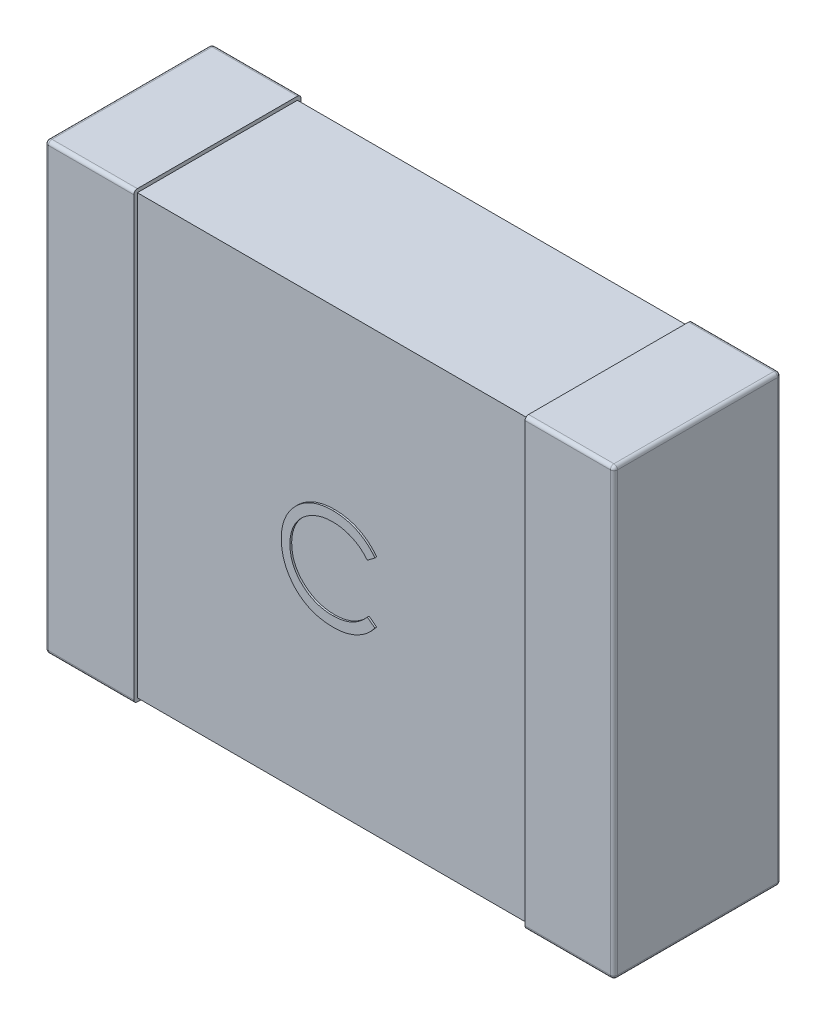
SolidWorks part; units mm, degrees
ref_plane "前视基准面" through (0, 0, 0) normal (0, 0, 1) x (1, 0, 0)
ref_plane "上视基准面" through (0, 0, 0) normal (0, 1, 0) x (1, 0, 0)
ref_plane "右视基准面" through (0, 0, 0) normal (1, 0, 0) x (0, 0, -1)
sketch "草图3" plane through (0, 0, 0) normal (0, 0, 1) x (1, 0, 0)
  line L0 (0, 0.9202) -> (0, -0.6542) construction
  line L1 (-1.6, 1.25) -> (-1.1, 1.25)
  line L2 (-1.6, 1.25) -> (-1.6, -1.25)
  line L3 (-1.6, -1.25) -> (-1.1, -1.25)
  line L4 (-1.1, 1.25) -> (-1.1, -1.25)
  line L5 (-1.6, 1.25) -> (-1.1, -1.25) construction
  line L6 (-1.6, -1.25) -> (-1.1, 1.25) construction
  line L7 (1.6, -1.25) -> (1.1, 1.25) construction
  line L8 (1.6, 1.25) -> (1.1, -1.25) construction
  line L9 (1.1, 1.25) -> (1.1, -1.25)
  line L10 (1.6, -1.25) -> (1.1, -1.25)
  line L11 (1.6, 1.25) -> (1.6, -1.25)
  line L12 (1.6, 1.25) -> (1.1, 1.25)
  point P0 (-1.35, 0)
  point P12 (1.35, 0)
  dimension "D1" = 0.5
  dimension "D2" = 2.5
  dimension "D3" = 1.6
extrude "凸台-拉伸1" add sketch "草图3" along normal blind 0.92 and the other way blind 0.02
sketch "草图5" plane through (0, 0, 0) normal (1, 0, 0) x (0, 0, -1)
  line L0 (0, 1.23) -> (0, -1.23)
  line L1 (0, -1.23) -> (-0.9, -1.23)
  line L2 (-0.9, -1.23) -> (-0.9, 1.23)
  line L3 (-0.9, 1.23) -> (0, 1.23)
  dimension "D1" = 2.46
  dimension "D2" = 0.9
extrude "凸台-拉伸3" add sketch "草图5" along normal mid plane 2.22
fillet "圆角3" radius 0.02 16 edges at (1.6, 0, -0.02) (1.6, -1.25, 0.45) (1.6, 0, 0.92) (1.6, 1.25, 0.45) (-1.6, 0, -0.02) (-1.6, 1.25, 0.45) (-1.6, 0, 0.92) (-1.6, -1.25, 0.45) (1.35, 1.25, -0.02) (1.35, -1.25, -0.02) (1.35, -1.25, 0.92) (1.35, 1.25, 0.92) (-1.35, -1.25, -0.02) (-1.35, -1.25, 0.92) (-1.35, 1.25, -0.02) (-1.35, 1.25, 0.92)
sketch "草图6" plane through (0, 0, 0.9) normal (0, 0, 1) x (1, 0, 0)
  text T0 "C" font "Century Gothic" height 0.54
extrude "凸台-拉伸4" add sketch "草图6" along normal blind 0.01
